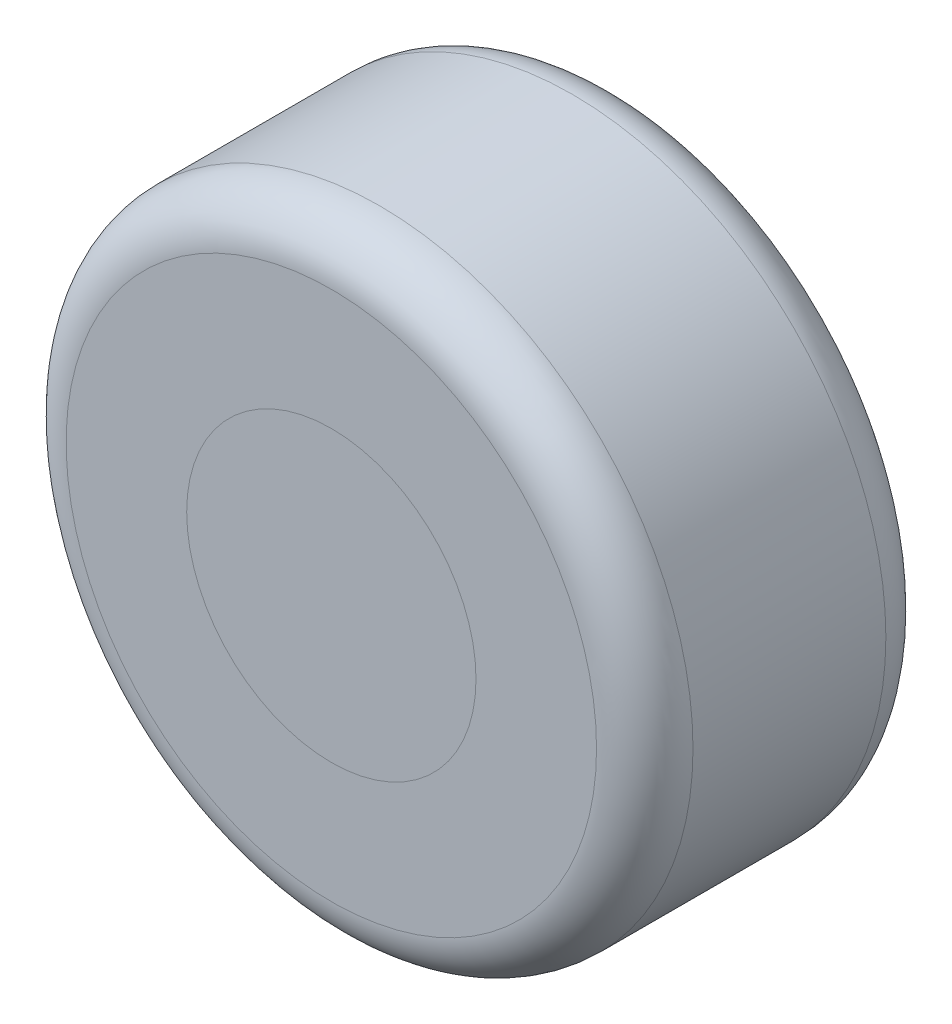
SolidWorks part; units mm, degrees
ref_plane "Front Plane" through (0, 0, 0) normal (0, 0, 1) x (1, 0, 0)
ref_plane "Top Plane" through (0, 0, 0) normal (0, 1, 0) x (1, 0, 0)
ref_plane "Right Plane" through (0, 0, 0) normal (1, 0, 0) x (0, 0, -1)
sketch "Sketch1" plane through (0, 0, 0) normal (0, 0, 1) x (1, 0, 0)
  circle A0 centre (0, 0) radius 65
  circle A1 centre (0, 0) radius 30
  dimension "D1" = 130
  dimension "D2" = 60
extrude "Boss-Extrude1" add sketch "Sketch1" against normal blind 60
fillet "Fillet1" radius 10 2 edges at (65, 0, -60) (65, 0, 0)
sketch "Sketch2" plane through (0, 0, 0) normal (0, 0, 1) x (1, 0, 0)
  circle A0 centre (0, 0) radius 30
extrude "Boss-Extrude3" add sketch "Sketch2" against normal blind 60 separate body contours A0
